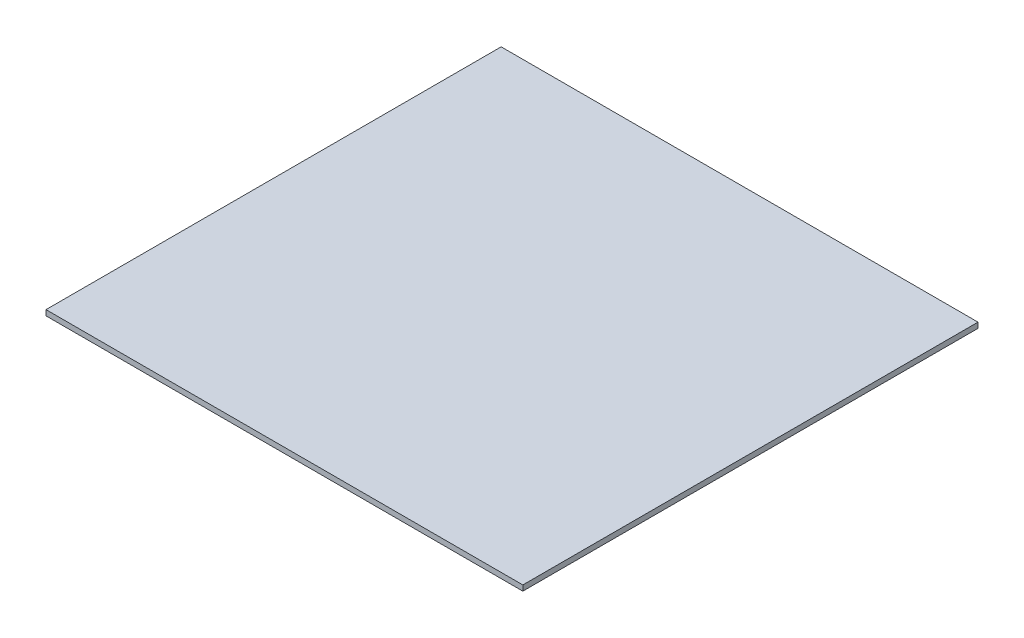
SolidWorks part; units mm, degrees
ref_plane "Front Plane" through (0, 0, 0) normal (0, 0, 1) x (1, 0, 0)
ref_plane "Top Plane" through (0, 0, 0) normal (0, 1, 0) x (1, 0, 0)
ref_plane "Right Plane" through (0, 0, 0) normal (1, 0, 0) x (0, 0, -1)
sketch "Sketch1" plane through (0, 0, 0) normal (0, 1, 0) x (1, 0, 0)
  line L1 (-279.4, -266.7) -> (279.4, -266.7)
  line L2 (-279.4, -266.7) -> (-279.4, 266.7)
  line L3 (-279.4, 266.7) -> (279.4, 266.7)
  line L4 (279.4, -266.7) -> (279.4, 266.7)
  line L5 (-279.4, -266.7) -> (279.4, 266.7) construction
  line L6 (-279.4, 266.7) -> (279.4, -266.7) construction
  point P0 (0, 0)
  dimension "D1" = 558.8
  dimension "D2" = 533.4
extrude "Boss-Extrude1" add sketch "Sketch1" along normal blind 6.35
